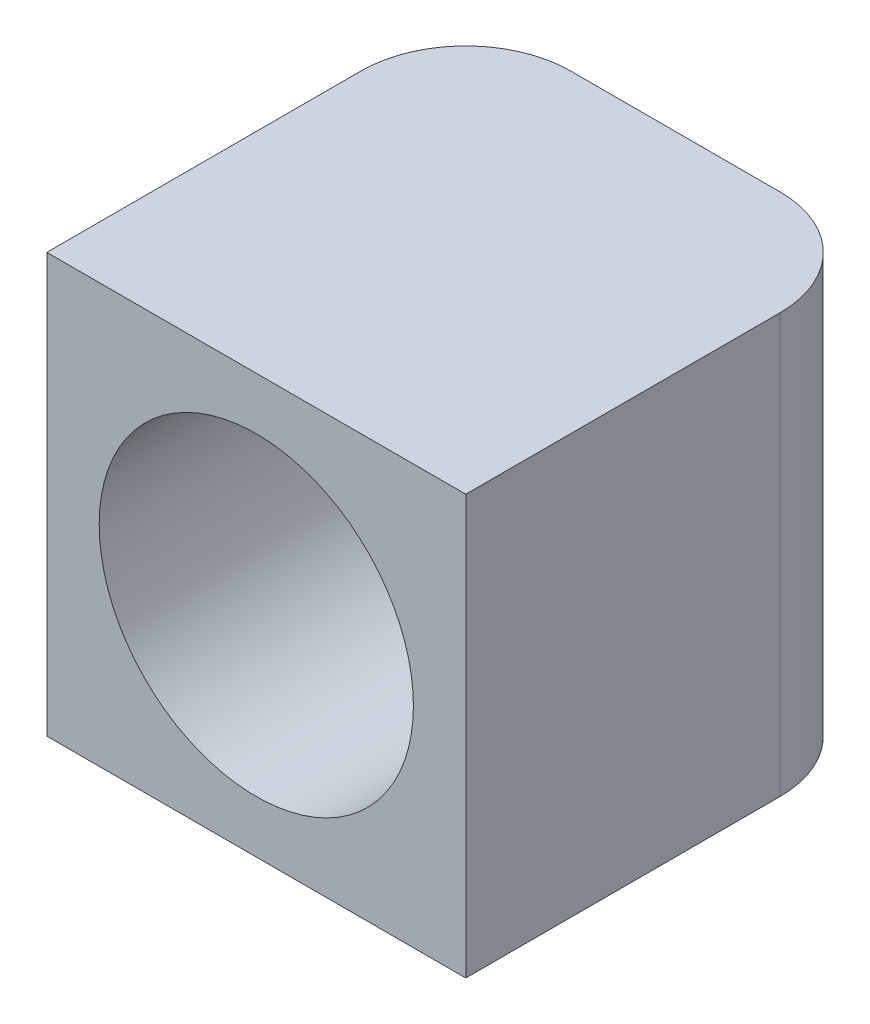
SolidWorks part; units mm, degrees
ref_plane "Front Plane" through (0, 0, 0) normal (0, 0, 1) x (1, 0, 0)
ref_plane "Top Plane" through (0, 0, 0) normal (0, 1, 0) x (1, 0, 0)
ref_plane "Right Plane" through (0, 0, 0) normal (1, 0, 0) x (0, 0, -1)
sketch "Sketch2" plane through (0, 0, 0) normal (1, 0, 0) x (0, 0, -1)
  line L1 (0, 0) -> (4, 0)
  line L2 (0, 0) -> (0, 4)
  line L3 (0, 4) -> (4, 4)
  line L4 (4, 0) -> (4, 4)
  dimension "D1" = 4
  dimension "D2" = 4
extrude "Boss-Extrude1" add sketch "Sketch2" along normal blind 4
fillet "Fillet1" radius 1 2 edges at (0, 2, -4) (4, 2, -4)
sketch "Sketch3" plane through (0, 0, 0) normal (0, 0, 1) x (1, 0, 0)
  line L0 (2, 4) -> (2, 0) construction
  line L1 (4, 4) -> (0, 4) construction
  line L2 (4, 0) -> (0, 0) construction
  circle A0 centre (2, 2) radius 1.5
  dimension "D2" = 3
  dimension "D1" = 2
extrude "Cut-Extrude1" cut sketch "Sketch3" against normal blind 3
